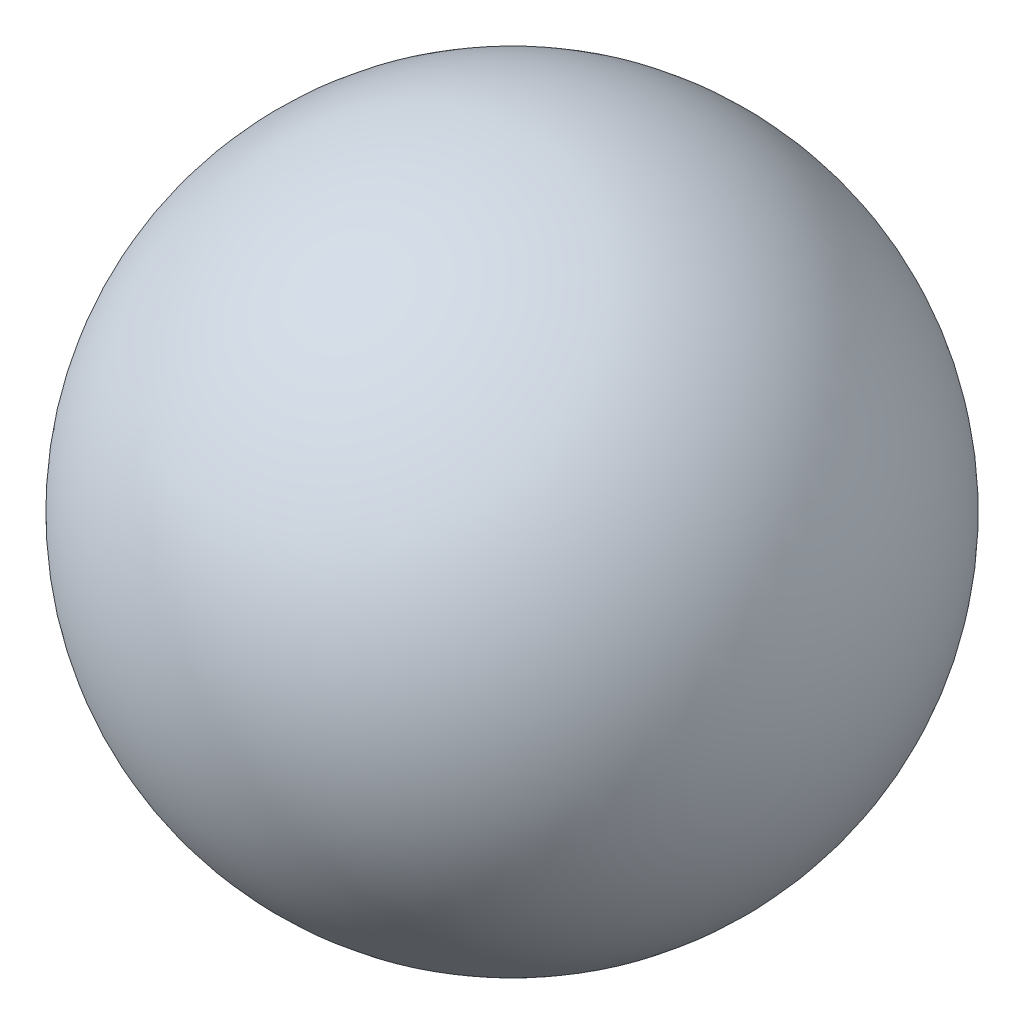
SolidWorks part; units mm, degrees
ref_plane "前视基准面" through (0, 0, 0) normal (0, 0, 1) x (1, 0, 0)
ref_plane "上视基准面" through (0, 0, 0) normal (0, 1, 0) x (1, 0, 0)
ref_plane "右视基准面" through (0, 0, 0) normal (1, 0, 0) x (0, 0, -1)
other "Configuration Table"
sketch "草图1" plane through (0, 0, 0) normal (0, 0, 1) x (1, 0, 0)
  line L0 (0, 105) -> (0, -105)
  arc A0 (0, -105) -> (0, 105) centre (0, 0) ccw
  dimension "D1" = 210
revolve "旋转1" add sketch "草图1" angle 360 about L0
